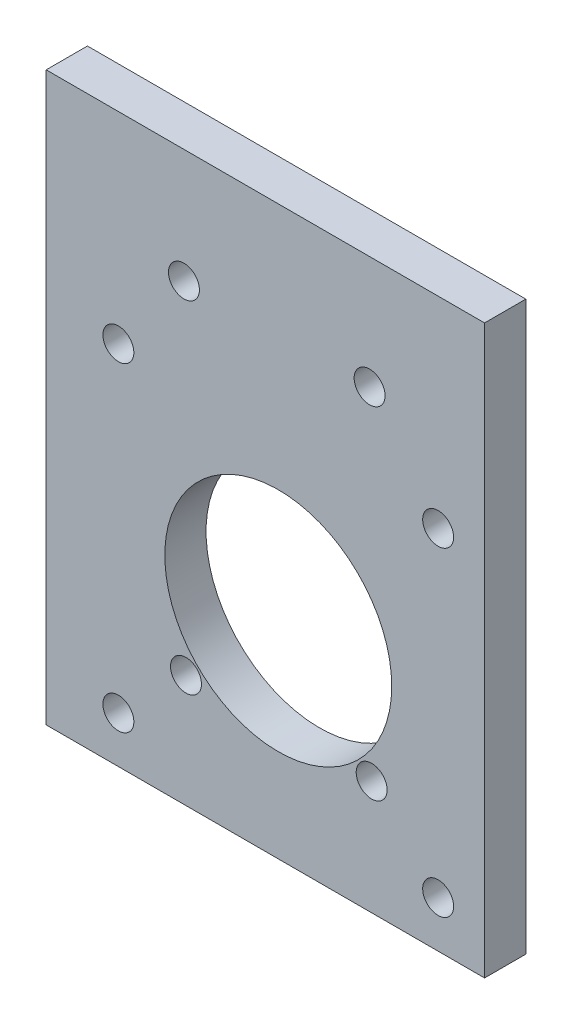
SolidWorks part; units mm, degrees
ref_plane "Front Plane" through (0, 0, 0) normal (0, 0, 1) x (1, 0, 0)
ref_plane "Top Plane" through (0, 0, 0) normal (0, 1, 0) x (1, 0, 0)
ref_plane "Right Plane" through (0, 0, 0) normal (1, 0, 0) x (0, 0, -1)
sketch "Sketch1" plane through (0, 0, 0) normal (0, 0, 1) x (1, 0, 0)
  line L1 (-21.25, 20) -> (21.25, 20)
  line L2 (-21.25, 20) -> (-21.25, -20)
  line L3 (-21.25, -20) -> (21.25, -20)
  line L4 (21.25, 20) -> (21.25, -20)
  line L5 (-21.25, 20) -> (21.25, -20) construction
  line L6 (-21.25, -20) -> (21.25, 20) construction
  point P0 (0, 0)
  dimension "D1" = 42.5
  dimension "D2" = 40
extrude "Boss-Extrude1" add sketch "Sketch1" along normal mid plane 4
sketch "Sketch2" plane through (0, 0, -2) normal (0, 0, -1) x (-1, 0, 0)
  line L0 (21.25, -20) -> (-21.25, -20) construction
  line L1 (-21.25, -20) -> (-21.25, 20) construction
  circle A0 centre (-16.75, 15.5) radius 1.5
  circle A1 centre (14.25, 15.5) radius 1.5
  circle A2 centre (14.25, -15.5) radius 1.5
  circle A3 centre (-16.75, -15.5) radius 1.5
  point P2 (0, 0)
  point P5 (0, 0)
  point P8 (0, 0)
  point P11 (0, 0)
  point P14 (0, 0)
  point P15 (0, 0)
  point P16 (0, 0)
  point P17 (0, 0)
  point P18 (0, 0)
  dimension "D1" = 3
  dimension "D2" = 31
  dimension "D3" = 31
  dimension "D4" = 4.5
  dimension "D5" = 4.5
extrude "Cut-Extrude1" cut sketch "Sketch2" against normal blind 4
sketch "Sketch3" plane through (0, 0, 2) normal (0, 0, 1) x (1, 0, 0)
  line L0 (21.25, -20) -> (21.25, 20) construction
  line L1 (-21.25, -20) -> (21.25, -20) construction
  circle A7 centre (1.25, 0) radius 11
  point P4 (0, 0)
  point P5 (0, 0)
  dimension "D2" = 20
  dimension "D1" = 20
extrude "Cut-Extrude2" cut sketch "Sketch3" against normal blind 4
sketch "Sketch4" plane through (0, 20, 0) normal (0, 1, 0) x (1, 0, 0)
  line L1 (-21.25, 2) -> (21.25, 2)
  line L2 (-21.25, 2) -> (-21.25, -2)
  line L3 (-21.25, -2) -> (21.25, -2)
  line L4 (21.25, 2) -> (21.25, -2)
extrude "Boss-Extrude2" add sketch "Sketch4" along normal blind 15
sketch "Sketch7" plane through (0, 0, 2) normal (0, 0, 1) x (1, 0, 0)
  circle A0 centre (-7.894, 23.9455) radius 1.5
  circle A1 centre (10.1057, 24.0536) radius 1.5
  circle A2 centre (10.3039, -8.9458) radius 1.5
  circle A3 centre (-7.6958, -9.0539) radius 1.5
  dimension "D1" = 3
extrude "Cut-Extrude3" cut sketch "Sketch7" against normal blind 10
